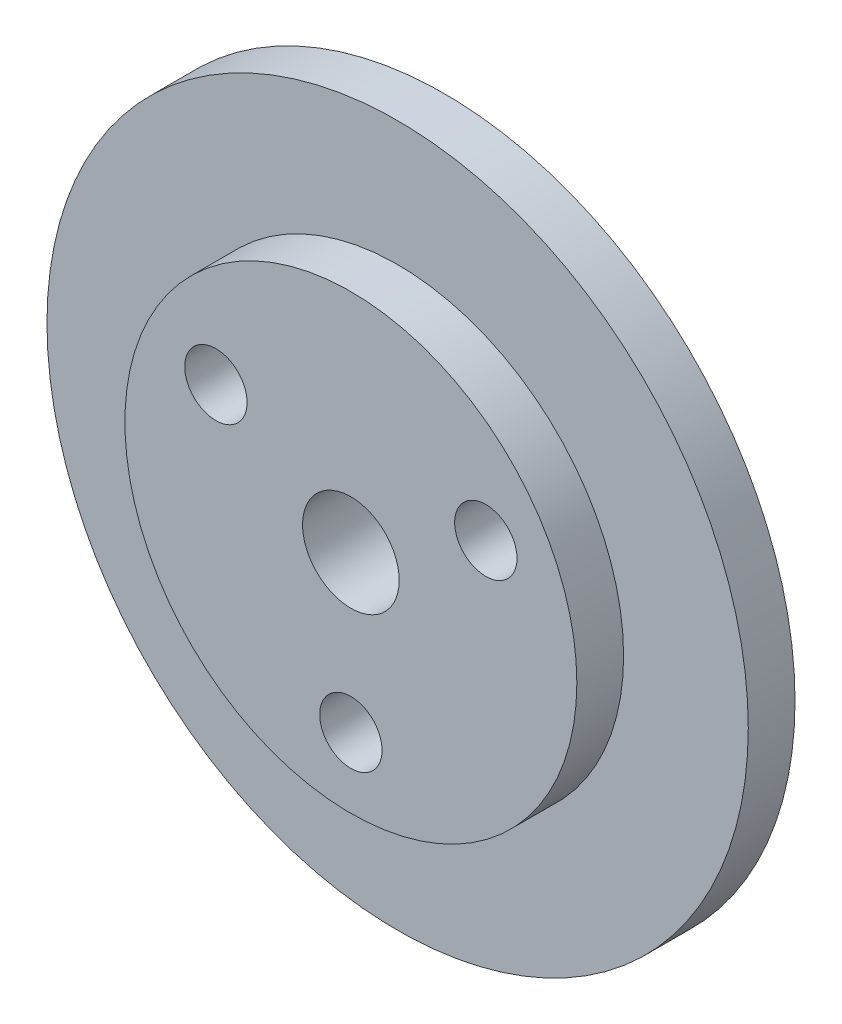
SolidWorks part; units mm, degrees
ref_plane "Plan de face" through (0, 0, 0) normal (0, 0, 1) x (1, 0, 0)
ref_plane "Plan de dessus" through (0, 0, 0) normal (0, 1, 0) x (1, 0, 0)
ref_plane "Plan de droite" through (0, 0, 0) normal (1, 0, 0) x (0, 0, -1)
sketch "Esquisse1" plane through (0, 0, 0) normal (0, 0, 1) x (1, 0, 0)
  line L0 (0, 0) -> (-45.0658, 26.0187) construction
  line L1 (0, 0) -> (42.4756, 24.5233) construction
  line L2 (0, 0) -> (0, -54.477) construction
  circle A0 centre (0, 0) radius 14.5 construction
  circle A1 centre (0, 0) radius 22.5
  circle A3 centre (0, 0) radius 10 construction
  dimension "D1" = 120
  dimension "D2" = 120
extrude "Boss.-Extru.1" add sketch "Esquisse1" along normal blind 3
sketch "Esquisse2" plane through (0, 0, 3) normal (0, 0, 1) x (1, 0, 0)
  circle A0 centre (0, 0) radius 14.5
extrude "Boss.-Extru.2" add sketch "Esquisse2" along normal blind 3
sketch "Esquisse3" plane through (0, 0, 6) normal (0, 0, 1) x (1, 0, 0)
  line L0 (0, 0) -> (42.4756, 24.5233) construction
  line L1 (0, 0) -> (-45.0658, 26.0187) construction
  line L2 (0, 0) -> (0, -54.477) construction
  circle A0 centre (8.6603, 5) radius 2
  circle A1 centre (0, 0) radius 10 construction
  circle A2 centre (-8.6603, 5) radius 2
  circle A3 centre (0, -10) radius 2
  circle A4 centre (0, 0) radius 3.1
extrude "Enlèv. mat.-Extru.1" cut sketch "Esquisse3" against normal through all
